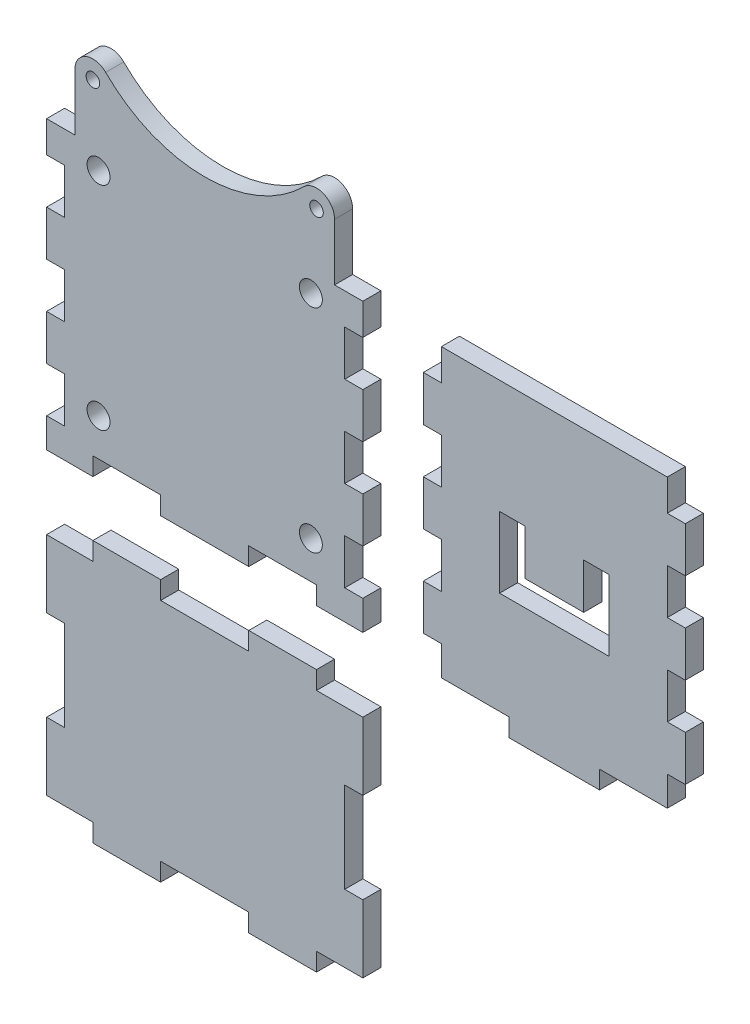
SolidWorks part; units mm, degrees
ref_plane "Front Plane" through (0, 0, 0) normal (0, 0, 1) x (1, 0, 0)
ref_plane "Top Plane" through (0, 0, 0) normal (0, 1, 0) x (1, 0, 0)
ref_plane "Right Plane" through (0, 0, 0) normal (1, 0, 0) x (0, 0, -1)
sketch "Sketch1" plane through (0, 0, 0) normal (0, 0, 1) x (1, 0, 0)
  line L0 (-24.7487, -24.7487) -> (0, 0) construction
  line L1 (0, 0) -> (24.7487, -24.7487) construction
  line L2 (0, -37.3307) -> (0, -35) construction
  line L3 (-35, -100.8307) -> (35, -100.8307)
  line L4 (-28.7487, -24.7487) -> (-28.7487, -37.3307)
  line L5 (-35, -64.2788) -> (-31, -64.2788)
  line L6 (28.7487, -24.7487) -> (28.7487, -37.3307)
  line L7 (-35, -100.8307) -> (-35, -37.3307)
  line L8 (-35, -37.3307) -> (-28.7487, -37.3307)
  line L9 (35, -100.8307) -> (35, -37.3307)
  line L10 (-23.5, -41.5497) -> (23.5, -41.5497) construction
  line L11 (-35, -44.2788) -> (-31, -44.2788)
  line L12 (-35, -44.2788) -> (-35, -54.2788)
  line L13 (-35, -54.2788) -> (-31, -54.2788)
  line L14 (-31, -44.2788) -> (-31, -54.2788)
  line L15 (23.5, -41.5497) -> (23.5, -88.5497) construction
  line L16 (23.5, -88.5497) -> (-23.5, -88.5497) construction
  line L17 (-23.5, -88.5497) -> (-23.5, -41.5497) construction
  line L18 (0, -37.3307) -> (0, -41.5497) construction
  line L19 (28.7487, -37.3307) -> (35, -37.3307)
  line L20 (-35, -64.2788) -> (-35, -74.2788)
  line L21 (-31, -64.2788) -> (-31, -74.2788)
  line L22 (-35, -74.2788) -> (-31, -74.2788)
  line L23 (-35, -84.2788) -> (-31, -84.2788)
  line L24 (-35, -84.2788) -> (-35, -94.2788)
  line L25 (-31, -84.2788) -> (-31, -94.2788)
  line L26 (-35, -94.2788) -> (-31, -94.2788)
  line L27 (35, -64.2788) -> (31, -64.2788)
  line L28 (35, -44.2788) -> (31, -44.2788)
  line L29 (35, -44.2788) -> (35, -54.2788)
  line L30 (35, -54.2788) -> (31, -54.2788)
  line L31 (31, -44.2788) -> (31, -54.2788)
  line L32 (31, -64.2788) -> (31, -74.2788)
  line L33 (35, -74.2788) -> (31, -74.2788)
  line L34 (35, -84.2788) -> (31, -84.2788)
  line L35 (31, -84.2788) -> (31, -94.2788)
  line L36 (35, -94.2788) -> (31, -94.2788)
  line L37 (-9.7487, -96.8307) -> (9.7487, -96.8307) construction
  line L38 (-24.7487, -100.8307) -> (-9.7487, -100.8307)
  line L39 (-24.7487, -100.8307) -> (-24.7487, -96.8307)
  line L40 (-24.7487, -96.8307) -> (-9.7487, -96.8307)
  line L41 (-9.7487, -100.8307) -> (-9.7487, -96.8307)
  line L42 (9.7487, -100.8307) -> (24.7487, -100.8307)
  line L43 (9.7487, -100.8307) -> (9.7487, -96.8307)
  line L44 (9.7487, -96.8307) -> (24.7487, -96.8307)
  line L45 (24.7487, -100.8307) -> (24.7487, -96.8307)
  line L46 (-24.7487, -96.8307) -> (-35, -96.8307) construction
  line L47 (0, -88.5497) -> (0, -96.8307) construction
  line L48 (24.7487, -96.8307) -> (35, -96.8307) construction
  line L49 (87.3929, -100.8307) -> (102.3929, -100.8307)
  line L50 (52.3929, -37.3307) -> (102.3929, -37.3307)
  line L51 (52.3929, -37.3307) -> (52.3929, -44.2788)
  line L52 (52.3929, -100.8307) -> (67.3929, -100.8307)
  line L53 (102.3929, -37.3307) -> (102.3929, -44.2788)
  line L54 (52.3929, -44.2788) -> (48.3929, -44.2788)
  line L55 (102.3929, -54.2788) -> (102.3929, -64.2788)
  line L56 (52.3929, -54.2788) -> (48.3929, -54.2788)
  line L57 (48.3929, -44.2788) -> (48.3929, -54.2788)
  line L58 (52.3929, -64.2788) -> (48.3929, -64.2788)
  line L59 (52.3929, -94.2788) -> (52.3929, -100.8307)
  line L60 (52.3929, -74.2788) -> (48.3929, -74.2788)
  line L61 (48.3929, -64.2788) -> (48.3929, -74.2788)
  line L62 (52.3929, -84.2788) -> (48.3929, -84.2788)
  line L63 (102.3929, -94.2788) -> (102.3929, -100.8307)
  line L64 (52.3929, -94.2788) -> (48.3929, -94.2788)
  line L65 (48.3929, -84.2788) -> (48.3929, -94.2788)
  line L66 (106.3929, -44.2788) -> (102.3929, -44.2788)
  line L67 (106.3929, -44.2788) -> (106.3929, -54.2788)
  line L68 (106.3929, -54.2788) -> (102.3929, -54.2788)
  line L69 (102.3929, -74.2788) -> (102.3929, -84.2788)
  line L70 (102.3929, -64.2788) -> (106.3929, -64.2788)
  line L71 (52.3929, -74.2788) -> (52.3929, -84.2788)
  line L72 (102.3929, -74.2788) -> (106.3929, -74.2788)
  line L73 (106.3929, -64.2788) -> (106.3929, -74.2788)
  line L74 (102.3929, -84.2788) -> (106.3929, -84.2788)
  line L75 (31, -132.0703) -> (31, -117.0703) construction
  line L76 (102.3929, -94.2788) -> (106.3929, -94.2788)
  line L77 (106.3929, -84.2788) -> (106.3929, -94.2788)
  line L78 (52.3929, -54.2788) -> (52.3929, -64.2788)
  line L79 (67.3929, -100.8307) -> (67.3929, -104.8307)
  line L80 (67.3929, -104.8307) -> (87.3929, -104.8307)
  line L81 (87.3929, -100.8307) -> (87.3929, -104.8307)
  line L82 (-35, -117.0703) -> (35, -117.0703)
  line L83 (-35, -117.0703) -> (-35, -167.0703)
  line L84 (-35, -167.0703) -> (35, -167.0703)
  line L85 (35, -117.0703) -> (35, -167.0703)
  line L86 (-24.7487, -117.0703) -> (-9.7487, -117.0703)
  line L87 (-24.7487, -117.0703) -> (-24.7487, -113.0703)
  line L88 (-24.7487, -113.0703) -> (-9.7487, -113.0703)
  line L89 (-9.7487, -117.0703) -> (-9.7487, -113.0703)
  line L90 (9.7487, -117.0703) -> (24.7487, -117.0703)
  line L91 (9.7487, -117.0703) -> (9.7487, -113.0703)
  line L92 (9.7487, -113.0703) -> (24.7487, -113.0703)
  line L93 (24.7487, -117.0703) -> (24.7487, -113.0703)
  line L94 (-24.7487, -167.0703) -> (-9.7487, -167.0703)
  line L95 (-24.7487, -167.0703) -> (-24.7487, -171.0703)
  line L96 (-24.7487, -171.0703) -> (-9.7487, -171.0703)
  line L97 (-9.7487, -167.0703) -> (-9.7487, -171.0703)
  line L98 (9.7487, -167.0703) -> (24.7487, -167.0703)
  line L99 (9.7487, -167.0703) -> (9.7487, -171.0703)
  line L100 (9.7487, -171.0703) -> (24.7487, -171.0703)
  line L101 (24.7487, -167.0703) -> (24.7487, -171.0703)
  line L102 (35, -132.0703) -> (31, -132.0703)
  line L103 (35, -132.0703) -> (35, -152.0703)
  line L104 (35, -152.0703) -> (31, -152.0703)
  line L105 (31, -132.0703) -> (31, -152.0703)
  line L106 (-35, -132.0703) -> (-31, -132.0703)
  line L107 (-35, -132.0703) -> (-35, -152.0703)
  line L108 (-35, -152.0703) -> (-31, -152.0703)
  line L109 (-31, -132.0703) -> (-31, -152.0703)
  line L110 (31, -152.0703) -> (31, -167.0703) construction
  line L111 (65.2727, -78.1598) -> (52.3929, -78.1598) construction
  line L112 (65.2727, -62.4817) -> (70.8931, -62.4817)
  line L113 (65.2727, -62.4817) -> (65.2727, -78.1598)
  line L114 (65.2727, -78.1598) -> (70.8931, -78.1598)
  line L115 (70.8931, -62.4817) -> (70.8931, -78.1598)
  line L116 (83.8928, -62.4817) -> (89.5132, -62.4817)
  line L117 (83.8928, -62.4817) -> (83.8928, -78.1598)
  line L118 (83.8928, -78.1598) -> (89.5132, -78.1598)
  line L119 (89.5132, -62.4817) -> (89.5132, -78.1598)
  line L120 (70.8931, -78.1598) -> (83.8928, -78.1598)
  line L121 (70.8931, -78.1598) -> (70.8931, -72.5394)
  line L122 (70.8931, -72.5394) -> (83.8928, -72.5394)
  line L123 (83.8928, -78.1598) -> (83.8928, -72.5394)
  line L124 (89.5132, -78.1598) -> (102.3929, -78.1598) construction
  line L125 (77.3929, -72.5394) -> (77.3929, -78.1598) construction
  circle A0 centre (0, 0) radius 30 construction
  circle A1 centre (-24.7487, -24.7487) radius 5 construction
  circle A2 centre (24.7487, -24.7487) radius 5 construction
  circle A3 centre (-24.7487, -24.7487) radius 1.5
  circle A4 centre (24.7487, -24.7487) radius 1.5
  arc A5 (-24.7487, -24.7487) -> (24.7487, -24.7487) centre (0, 0) ccw construction
  circle A6 centre (23.5, -41.5497) radius 2.54
  arc A7 (-21.9203, -21.9203) -> (21.9203, -21.9203) centre (0, 0) ccw
  arc A8 (-21.9203, -21.9203) -> (-28.7487, -24.7487) centre (-24.7487, -24.7487) ccw
  arc A9 (28.7487, -24.7487) -> (21.9203, -21.9203) centre (24.7487, -24.7487) ccw
  circle A10 centre (23.5, -88.5497) radius 2.54
  circle A11 centre (-23.5, -88.5497) radius 2.54
  circle A12 centre (-23.5, -41.5497) radius 2.54
  point P10 (0, -35)
  dimension "D1" = 3
  dimension "D2" = 3
extrude "Boss-Extrude1" add sketch "Sketch1" along normal blind 4
